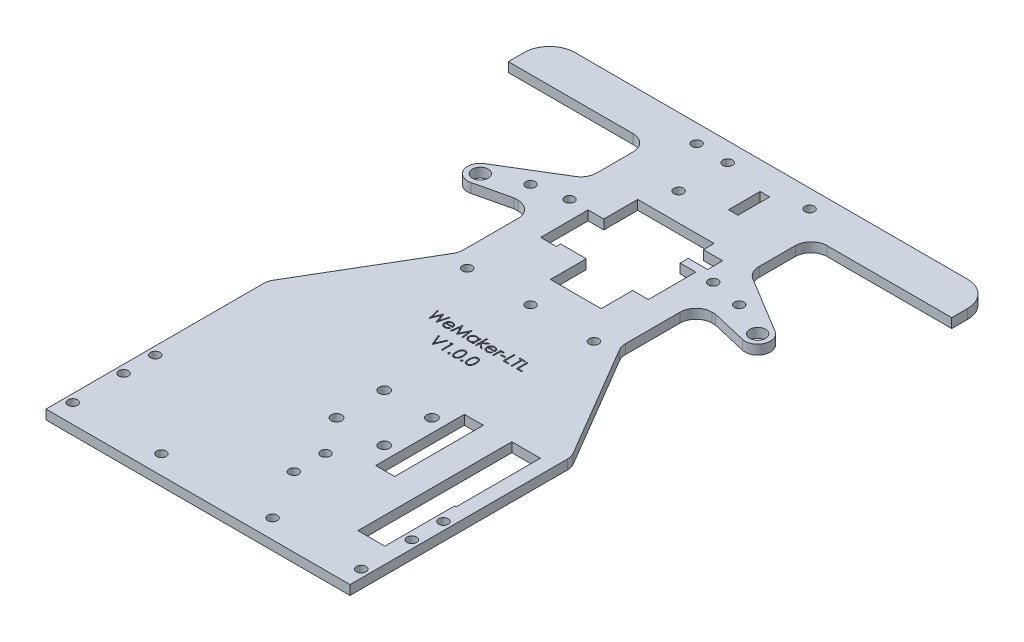
SolidWorks part; units mm, degrees
ref_plane "前基準面" through (0, 0, 0) normal (0, 0, 1) x (1, 0, 0)
ref_plane "上基準面" through (0, 0, 0) normal (0, 1, 0) x (1, 0, 0)
ref_plane "右基準面" through (0, 0, 0) normal (1, 0, 0) x (0, 0, -1)
sketch "Sketch1" plane through (0, 0, 0) normal (0, 1, 0) x (1, 0, 0)
  line L0 (43, -58) -> (48, -58) construction
  line L1 (-48, -80) -> (48, -80) construction
  line L2 (-48, -80) -> (-48, 80)
  line L3 (-48, 80) -> (48, 80)
  line L4 (48, -80) -> (48, 80)
  line L5 (0, 80) -> (0, -80) construction
  line L6 (-48, 0) -> (48, 0) construction
  line L7 (-48, -80) -> (48, -80) construction
  line L8 (-48, -80) -> (-48, -96)
  line L9 (-48, -96) -> (48, -96)
  line L10 (48, -80) -> (48, -96)
  line L11 (19.5, -31.4) -> (25.5, -31.4)
  line L12 (19.5, -31.4) -> (19.5, -59.4)
  line L13 (19.5, -59.4) -> (25.5, -59.4)
  line L14 (25.5, -31.4) -> (25.5, -59.4)
  line L15 (43, -80) -> (34.5, -80)
  line L16 (43, -80) -> (43, -31.4) construction
  line L17 (43, -31.4) -> (34.5, -31.4)
  line L18 (34.5, -80) -> (34.5, -31.4)
  line L19 (43, -31.4) -> (43.5, -31.4)
  line L20 (43, -31.4) -> (43, -58) construction
  line L21 (43, -58) -> (43.5, -58)
  line L22 (43.5, -31.4) -> (43.5, -58)
  line L23 (43, -80) -> (43, -58)
  circle A0 centre (45.5, -74) radius 1.5 construction
  circle A1 centre (45.5, -64) radius 1.5 construction
  circle A2 centre (-45.5, -64) radius 1.5 construction
  circle A3 centre (-45.5, -74) radius 1.5 construction
  circle A4 centre (45.5, -74) radius 1.5
  circle A5 centre (45.5, -64) radius 1.5
  circle A6 centre (-45.5, -64) radius 1.5
  circle A7 centre (-45.5, -74) radius 1.5
  circle A8 centre (8.25, -74) radius 1.5 construction
  circle A9 centre (8.25, -64) radius 1.5 construction
  circle A10 centre (8.25, -74) radius 1.5
  circle A11 centre (8.25, -64) radius 1.5
  circle A12 centre (15.3209, -52.5307) radius 1.65 construction
  circle A13 centre (0.2595, -52.5307) radius 1.65 construction
  circle A14 centre (15.3209, -37.4693) radius 1.65 construction
  circle A15 centre (0.2595, -37.4693) radius 1.65 construction
  circle A16 centre (15.3209, -52.5307) radius 1.65 construction
  circle A17 centre (0.2595, -52.5307) radius 1.65 construction
  circle A18 centre (15.3209, -37.4693) radius 1.65 construction
  circle A19 centre (0.2595, -37.4693) radius 1.65 construction
  circle A24 centre (0.2595, -37.4693) radius 1.65
  circle A25 centre (15.3209, -37.4693) radius 1.65
  circle A26 centre (15.3209, -52.5307) radius 1.65
  circle A27 centre (0.2595, -52.5307) radius 1.65
  circle A28 centre (17.55, -90) radius 1.5 construction
  circle A29 centre (17.55, -90) radius 1.5
  circle A30 centre (45.55, -90) radius 1.5 construction
  circle A31 centre (45.55, -90) radius 1.5
  circle A32 centre (-45.55, -90) radius 1.5
  circle A33 centre (-17.55, -90) radius 1.5
  point P0 (0, 0)
  dimension "D4" = 0.5
  dimension "D5" = 6
  dimension "D1" = 96
  dimension "D2" = 160
  dimension "D3" = 16
  dimension "D6" = 28
  dimension "D7" = 22.5
  dimension "D8" = 36.6
  dimension "D9" = 8.5
  dimension "D10" = 48.6
extrude "Boss-Extrude1" add sketch "Sketch1" along normal blind 3
sketch "Sketch3" plane through (0, 3, 0) normal (0, 1, 0) x (1, 0, 0)
  line L0 (0, -96) -> (0, 80) construction
  line L1 (-48, -96) -> (48, -96) construction
  line L2 (48, 80) -> (-48, 80) construction
  line L3 (0, 9) -> (-17.8495, 79.2684) construction
  line L4 (-17.8495, 79.2684) -> (17.8495, 79.2684) construction
  line L5 (0, 9) -> (17.8495, 79.2684) construction
  circle A0 centre (0, 9) radius 5 construction
  circle A1 centre (0, 9) radius 1.5
  circle A2 centre (-17.8495, 79.2684) radius 0.7646 construction
  circle A3 centre (17.8495, 79.2684) radius 1.5 construction
  point P12 (0, 79.2684)
  dimension "D1" = 10
  dimension "D2" = 105
  dimension "D3" = 3
  dimension "D6" = 3
  dimension "D7" = 1.5291
  dimension "D4" = 72.5
  dimension "D5" = 17.8495
extrude "Cut-Extrude2" cut sketch "Sketch3" against normal up to next
sketch "Sketch4" plane through (0, 3, 0) normal (0, 1, 0) x (1, 0, 0)
  line L0 (0, 80) -> (0, 0) construction
  line L1 (48, 80) -> (-48, 80) construction
  line L2 (48, 12) -> (25.605, 12)
  line L3 (-48, 80) -> (-25.605, 80)
  line L4 (-48, 80) -> (-48, 12)
  line L5 (-48, 12) -> (-25.605, 12)
  line L6 (-25.605, 80) -> (-25.605, 12)
  line L7 (25.605, 80) -> (25.605, 12)
  line L8 (48, 80) -> (25.605, 80)
  line L9 (48, 80) -> (48, 12)
  dimension "D1" = 51.21
  dimension "D2" = 68
extrude "Cut-Extrude3" cut sketch "Sketch4" against normal up to next
sketch "Sketch6" plane through (0, 3, 0) normal (0, 1, 0) x (1, 0, 0)
  line L0 (25.605, 80) -> (25.605, 12) construction
  line L1 (-25.605, 80) -> (25.605, 80)
  line L2 (-25.605, 80) -> (-25.605, 85)
  line L3 (-25.605, 85) -> (25.605, 85)
  line L4 (25.605, 80) -> (25.605, 85)
  dimension "D1" = 5
extrude "Boss-Extrude2" add sketch "Sketch6" against normal blind 3
sketch "Sketch7" plane through (0, 3, 0) normal (0, 1, 0) x (1, 0, 0)
  circle A0 centre (-17.8495, 79.2684) radius 1.5
  circle A1 centre (17.8495, 79.2684) radius 1.5
  dimension "D1" = 3
  dimension "D2" = 3
extrude "Cut-Extrude4" cut sketch "Sketch7" against normal up to next
sketch "Sketch9" plane through (0, 3, 0) normal (0, 1, 0) x (1, 0, 0)
  line L2 (25.605, 85) -> (-25.605, 85) construction
  line L4 (-22.6908, 44) -> (-25.605, 44) construction
  line L5 (-25.605, 12) -> (-25.605, 85) construction
  line L6 (-22.6908, 44) -> (-22.6908, 32.9821) construction
  line L7 (0, 85) -> (0, 0) construction
  circle A1 centre (-22.6908, 44) radius 1.5
  circle A2 centre (22.6908, 44) radius 1.5
  dimension "D1" = 3
  dimension "D2" = 41
extrude "Cut-Extrude5" cut sketch "Sketch9" against normal up to next
sketch "Sketch10" plane through (0, 3, 0) normal (0, 1, 0) x (1, 0, 0)
  line L0 (0, 85) -> (0, -96) construction
  line L1 (25.605, 85) -> (-25.605, 85) construction
  line L2 (-48, -96) -> (48, -96) construction
  line L3 (48, -26) -> (25.605, 12)
  line L4 (48, -96) -> (48, 12) construction
  line L5 (48, -26) -> (48, 12)
  line L6 (48, 12) -> (25.605, 12)
  line L7 (-48, -26) -> (-48, 12)
  line L8 (-48, -26) -> (-25.605, 12)
  line L9 (-48, 12) -> (-25.605, 12)
  dimension "D1" = 38
extrude "Cut-Extrude6" cut sketch "Sketch10" against normal up to next
sketch "Sketch11" plane through (0, 0, 0) normal (0, -1, 0) x (1, 0, 0)
  line L0 (-25.605, -52.6413) -> (-45.8738, -40.3515)
  line L1 (-45.8738, -40.3515) -> (-25.605, -52.6413) construction
  line L2 (-42.8854, -33.0371) -> (-31.7967, -35.6413)
  line L3 (-31.7967, -35.6413) -> (-25.605, -35.6413)
  line L4 (-16.2499, -35.6413) -> (-31.7967, -35.6413) construction
  line L5 (-25.605, -35.6413) -> (-25.605, -52.6413)
  line L6 (0, 0) -> (0, -85) construction
  line L7 (42.8854, -33.0371) -> (31.7967, -35.6413)
  line L8 (25.605, -12) -> (48, 26)
  line L9 (48, 26) -> (48, 96)
  line L10 (48, 96) -> (-48, 96)
  line L11 (-48, 96) -> (-48, 26)
  line L12 (-48, 26) -> (-25.605, -12)
  line L13 (-25.605, -12) -> (-25.605, -85)
  line L14 (-25.605, -85) -> (25.605, -85)
  line L15 (25.605, -85) -> (25.605, -12)
  line L16 (25.605, -12) -> (48, 26)
  line L17 (48, 26) -> (48, 96)
  line L18 (48, 96) -> (-48, 96)
  line L19 (-48, 96) -> (-48, 26)
  line L20 (-48, 26) -> (-25.605, -12)
  line L21 (-25.605, -12) -> (-25.605, -85)
  line L22 (-25.605, -85) -> (25.605, -85)
  line L23 (25.605, -85) -> (25.605, -12)
  line L24 (31.7967, -35.6413) -> (25.605, -35.6413)
  line L25 (25.605, -35.6413) -> (25.605, -52.6413)
  line L26 (25.605, -52.6413) -> (45.8738, -40.3515)
  arc A0 (-45.8738, -40.3515) -> (-42.8854, -33.0371) centre (-43.7999, -36.9312) cw
  circle A1 centre (-43.7999, -36.9312) radius 2.5
  circle A2 centre (-32.9303, -41.9312) radius 1.5
  circle A3 centre (32.9303, -41.9312) radius 1.5
  circle A4 centre (43.7999, -36.9312) radius 2.5
  arc A5 (45.8738, -40.3515) -> (42.8854, -33.0371) centre (43.7999, -36.9312) ccw
  line M26 (-25.605, -12) -> (-25.605, -85)
  dimension "D2" = 5
  dimension "D3" = 3
  dimension "D1" = 0
extrude "Boss-Extrude3" add sketch "Sketch11" against normal blind 3 contours A0 L0 L3 L2 A2 A1 M26 | L26 A5 L7 L24 L23 A4 A3
sketch "Sketch12" plane through (0, 0, 0) normal (0, -1, 0) x (1, 0, 0)
  line L0 (11.4001, -53.9413) -> (11.4001, -38.6413) construction
  line L1 (11.4001, -38.6413) -> (16.2501, -38.6413) construction
  line L2 (16.2501, -38.6413) -> (16.3501, -32.8413) construction
  line L3 (16.3501, -32.8413) -> (11.4001, -32.8413) construction
  line L4 (11.4001, -32.8413) -> (11.4001, -31.1913) construction
  line L5 (11.4001, -31.1913) -> (11.4001, -25.1913) construction
  line L6 (11.4001, -25.1913) -> (5.4001, -25.1913) construction
  line L7 (11.4001, -25.1913) -> (11.4001, -19.8913) construction
  line L8 (11.4001, -19.8913) -> (-2.9999, -19.8913) construction
  line L9 (-2.9999, -19.8913) -> (-2.9999, -31.1913) construction
  line L10 (-11.0999, -31.1913) -> (5.4001, -31.1913) construction
  line L11 (-2.9999, -31.1913) -> (-11.0999, -31.1913) construction
  line L12 (-11.0999, -31.1913) -> (-11.0999, -32.8413) construction
  line L13 (-11.0999, -32.8413) -> (-16.0499, -32.8413) construction
  line L14 (-16.0499, -32.8413) -> (-16.0499, -38.6413) construction
  line L15 (-15.2499, -38.6413) -> (-16.2499, -38.6413) construction
  line L16 (-16.0499, -38.6413) -> (-11.0999, -38.6413) construction
  line L17 (-11.0999, -53.9413) -> (-11.0999, -35.6413) construction
  line L18 (-11.0999, -38.6413) -> (-11.0999, -53.9413) construction
  line L19 (-11.0999, -53.9413) -> (11.4001, -53.9413) construction
  line L20 (-11.8999, -39.4413) -> (-11.8999, -54.7413)
  line L21 (-11.8999, -54.7413) -> (12.2001, -54.7413)
  line L22 (12.2001, -54.7413) -> (12.2001, -39.4413)
  line L23 (12.2001, -39.4413) -> (17.0364, -39.4413)
  line L24 (17.0364, -39.4413) -> (17.164, -32.0413)
  line L25 (17.164, -32.0413) -> (12.2001, -32.0413)
  line L26 (12.2001, -32.0413) -> (12.2001, -31.1913)
  line L27 (12.2001, -31.1913) -> (12.2001, -25.1913)
  line L28 (12.2001, -25.1913) -> (12.2001, -19.0913)
  line L29 (12.2001, -19.0913) -> (-3.7999, -19.0913)
  line L30 (-3.7999, -19.0913) -> (-3.7999, -30.3913)
  line L31 (-3.7999, -30.3913) -> (-11.8999, -30.3913)
  line L32 (-11.8999, -30.3913) -> (-11.8999, -32.0413)
  line L33 (-11.8999, -32.0413) -> (-16.8499, -32.0413)
  line L34 (-16.8499, -32.0413) -> (-16.8499, -39.4413)
  line L35 (-16.8499, -39.4413) -> (-11.8999, -39.4413)
  dimension "D2" = 16
  dimension "D3" = 11.3
  dimension "D1" = 0.8
extrude "Cut-Extrude7" cut sketch "Sketch12" against normal up to next
sketch "Sketch13" plane through (0, 0, 0) normal (0, -1, 0) x (1, 0, 0)
  line L0 (-11.8999, -39.4413) -> (-11.8999, -54.7413) construction
  line L1 (-16.8499, -29.0413) -> (-11.8999, -29.0413)
  line L2 (-16.8499, -29.0413) -> (-16.8499, -44.0413)
  line L3 (-16.8499, -44.0413) -> (-11.8999, -44.0413)
  line L4 (-11.8999, -29.0413) -> (-11.8999, -44.0413)
  line L5 (-16.8499, -32.0413) -> (-16.8499, -39.4413) construction
  line L6 (-11.8999, -32.0413) -> (-16.8499, -32.0413) construction
  line L7 (0.1501, -54.7413) -> (0.1501, -13.9321) construction
  line L8 (-11.8999, -54.7413) -> (12.2001, -54.7413) construction
  line L9 (17.1501, -29.0413) -> (17.1501, -44.0413)
  line L10 (17.1501, -29.0413) -> (12.2001, -29.0413)
  line L11 (12.2001, -29.0413) -> (12.2001, -44.0413)
  line L12 (17.1501, -44.0413) -> (12.2001, -44.0413)
  line L13 (12.2001, -54.7413) -> (12.2001, -39.4413) construction
  line L14 (12.2001, -51.376) -> (18.2789, -51.376)
  line L15 (12.2001, -51.376) -> (12.2001, -46.608)
  line L16 (12.2001, -46.608) -> (18.2789, -46.608)
  line L17 (18.2789, -51.376) -> (18.2789, -46.608)
  dimension "D1" = 3
  dimension "D2" = 15
extrude "Cut-Extrude8" cut sketch "Sketch13" against normal up to next
sketch "Sketch14" plane through (0, 0, 0) normal (0, -1, 0) x (1, 0, 0)
  line L0 (0, -85) -> (0, 0) construction
  line L1 (25.605, -85) -> (-25.605, -85) construction
  line L2 (25.605, -85) -> (25.605, -72)
  line L3 (70, -72) -> (-70, -72)
  line L4 (70, -72) -> (70, -77)
  line L5 (62, -85) -> (-62, -85)
  line L6 (-70, -72) -> (-70, -77)
  line L7 (0, -85) -> (0, -72) construction
  line L8 (70, -74.5) -> (-70, -74.5) construction
  line L9 (-25.605, -85) -> (-25.605, -72)
  arc A0 (70, -77) -> (62, -85) centre (62, -77) cw
  arc A1 (-62, -85) -> (-70, -77) centre (-62, -77) cw
  point P5 (0, -74.5)
  point P15 (70, -85)
  point P18 (-70, -85)
  dimension "D3" = 8
  dimension "D1" = 13
  dimension "D2" = 140
extrude "Boss-Extrude4" add sketch "Sketch14" against normal blind 3 contours A1 L5 L9 L3 L6 | A0 L4 L3 L2 L5
sketch "Sketch15" plane through (0, 3, 0) normal (0, 1, 0) x (1, 0, 0)
  line L0 (0, 0) -> (0, 85) construction
  line L1 (62, 85) -> (-62, 85) construction
  line L2 (20, 9) -> (-20, 9) construction
  circle A0 centre (-20, 9) radius 1.5
  circle A1 centre (20, 9) radius 1.5
  point P9 (0, 9)
  dimension "D2" = 3
  dimension "D1" = 40
extrude "Cut-Extrude9" cut sketch "Sketch15" against normal up to next
fillet "Fillet1" radius 5 10 edges at (-48, 1.5, 26) (-25.605, 1.5, -12) (-25.605, 1.5, -35.6413) (-25.605, 1.5, -52.6413) (-25.605, 1.5, -72) (25.605, 1.5, -72) (25.605, 1.5, -52.6413) (25.605, 1.5, -35.6413) (25.605, 1.5, -12) (48, 1.5, 26)
sketch "Sketch16" plane through (0, 3, 0) normal (0, 1, 0) x (1, 0, 0)
  line L0 (-13.4601, -10.7191) -> (17.6686, -10.7191) construction
  line L1 (-6.3823, -17.3846) -> (11.2092, -17.3846) construction
  text T0 "WeMaker-LTL"
  text T1 "V1.0.0"
  point P3 (-6.3823, -17.3846)
  point P4 (-5.1454, -17.1784)
extrude "Cut-Extrude10" cut sketch "Sketch16" against normal blind 0.5
sketch "Sketch17" plane through (0, 0, 0) normal (0, -1, 0) x (1, 0, 0)
  line L0 (0, -85) -> (0, 0) construction
  line L1 (62, -85) -> (-62, -85) construction
  line L3 (7.75, -63.5) -> (-7.75, -63.5) construction
  line L4 (7.75, -63.5) -> (7.75, -79) construction
  line L5 (7.75, -79) -> (-7.75, -79) construction
  line L6 (-7.75, -63.5) -> (-7.75, -79) construction
  line L7 (0, -79) -> (0, -63.5) construction
  line L8 (7.75, -71.25) -> (-7.75, -71.25) construction
  line L9 (5.25, -76.25) -> (8.25, -76.25)
  line L10 (5.25, -76.25) -> (5.25, -66.25)
  line L11 (5.25, -66.25) -> (8.25, -66.25)
  line L12 (8.25, -76.25) -> (8.25, -66.25)
  line L13 (6.75, -66.25) -> (6.75, -76.25) construction
  line L14 (5.25, -71.25) -> (8.25, -71.25) construction
  circle A0 centre (-7.75, -79) radius 1.5
  circle A1 centre (-7.75, -63.5) radius 1.5
  point P5 (0, -71.25)
  point P11 (6.75, -71.25)
  dimension "D4" = 3
  dimension "D5" = 3
  dimension "D1" = 15.5
  dimension "D2" = 15.5
  dimension "D3" = 6
  dimension "D6" = 3
  dimension "D7" = 10
  dimension "D8" = 0.5
extrude "Cut-Extrude11" cut sketch "Sketch17" against normal through all
